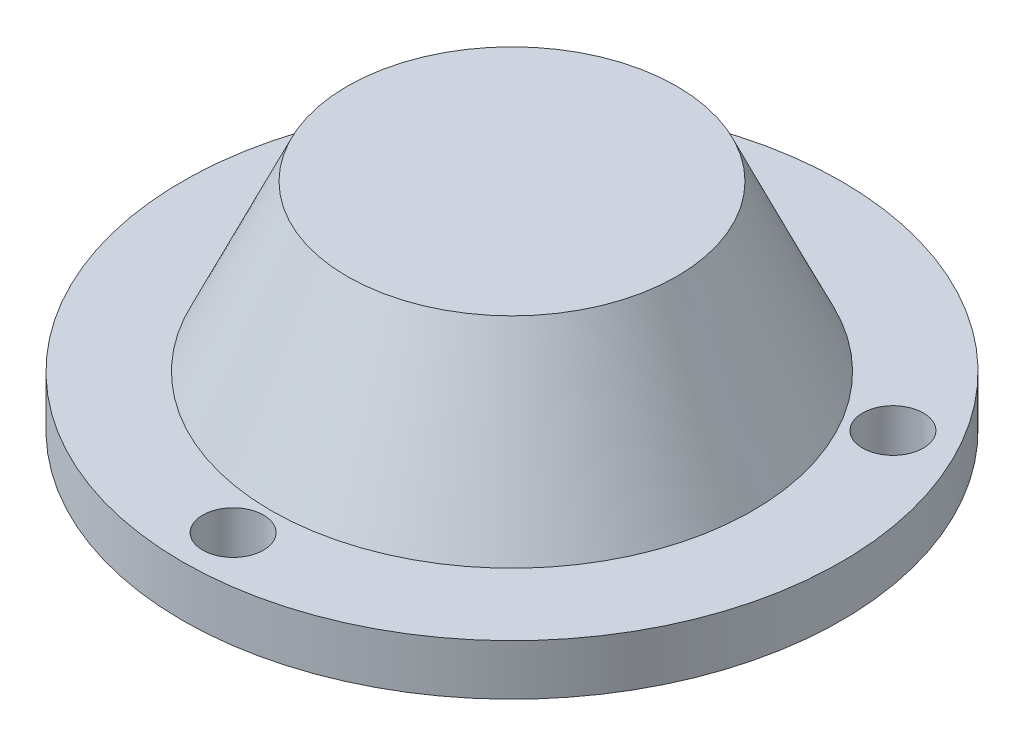
SolidWorks part; units mm, degrees
ref_plane "Front Plane" through (0, 0, 0) normal (0, 0, 1) x (1, 0, 0)
ref_plane "Top Plane" through (0, 0, 0) normal (0, 1, 0) x (1, 0, 0)
ref_plane "Right Plane" through (0, 0, 0) normal (1, 0, 0) x (0, 0, -1)
sketch "Sketch1" plane through (0, 0, 0) normal (0, 0, 1) x (1, 0, 0)
  line L0 (-6.5, 8.5) -> (6.5, 8.5)
  line L1 (6.5, 8.5) -> (9.5, 2)
  line L2 (9.5, 2) -> (13, 2)
  line L3 (13, 2) -> (13, 0)
  line L4 (13, 0) -> (-13, 0)
  line L5 (-13, 0) -> (-13, 2)
  line L6 (-13, 2) -> (-9.5, 2)
  line L7 (-9.5, 2) -> (-6.5, 8.5)
  line L8 (0, 8.5) -> (0, -7)
  line L9 (5.7793, -3.2079) -> (5.9967, -3.2079)
  arc A0 (-6.261, 0) -> (6.261, 0) centre (0, -0.7) ccw
  arc A4 (5.9967, -3.2079) -> (5.9127, 0) centre (-0.342, -1.7689) ccw
  point P2 (0, 8.5)
  point P9 (0, 0)
  dimension "D6" = 12.6
  dimension "D1" = 2
  dimension "D2" = 13
  dimension "D3" = 6.5
  dimension "D4" = 26
  dimension "D7" = 0.7
  dimension "D5" = 19
revolve "Revolve1" add sketch "Sketch1" angle 360 about L8
fillet "Fillet1" radius 3 1 edges at (0, 0, 5.9127)
sketch "Sketch2" plane through (0, 0, 0) normal (0, -1, 0) x (1, 0, 0)
  circle A0 centre (0, 11) radius 1.2
  circle A1 centre (9.5263, -5.5) radius 1.2
  circle A2 centre (-9.5263, -5.5) radius 1.2
  point P9 (0, 0)
  dimension "D1" = 2.4
  dimension "D2" = 11
  dimension "D3" = 3
extrude "Cut-Extrude1" cut sketch "Sketch2" against normal blind 10
equation "\"D7@Sketch1\"=7-6.3"
